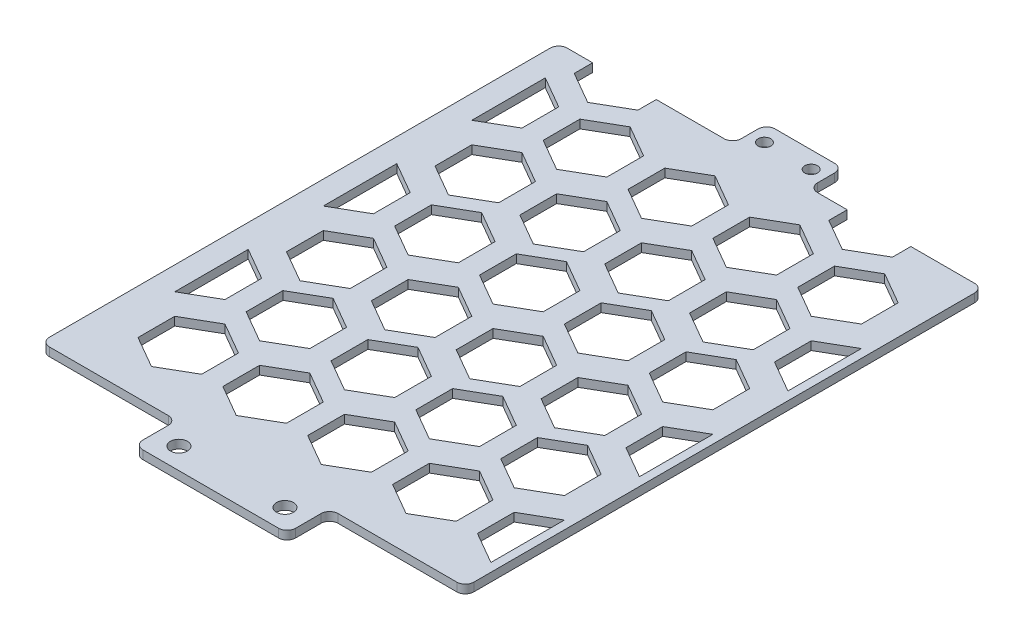
SolidWorks part; units mm, degrees
material "Thornel Mat VMA"
ref_plane "前视基准面" through (0, 0, 0) normal (0, 0, 1) x (1, 0, 0)
ref_plane "上视基准面" through (0, 0, 0) normal (0, 1, 0) x (1, 0, 0)
ref_plane "右视基准面" through (0, 0, 0) normal (1, 0, 0) x (0, 0, -1)
other "Configuration Table"
sketch "草图1" plane through (0, 0, 0) normal (0, 1, 0) x (1, 0, 0)
  line L0 (0, 0) -> (0, 39.2734) construction
  line L1 (50, -70) -> (18, -70)
  line L2 (50, -70) -> (50, 70)
  line L3 (50, 70) -> (-50, 70)
  line L4 (-50, -70) -> (-50, 70)
  line L5 (50, -70) -> (-50, 70) construction
  line L6 (50, 70) -> (-50, -70) construction
  line L7 (-18, -70) -> (-18, -80)
  line L8 (-18, -80) -> (18, -80)
  line L9 (18, -80) -> (18, -70)
  line L10 (0, -80) -> (0, -62.3533) construction
  line L11 (-18, -70) -> (-50, -70)
  circle A0 centre (-42.5, 66) radius 1.5
  circle A1 centre (42.5, 66) radius 1.5
  circle A2 centre (-12.5, -75) radius 2
  circle A3 centre (12.5, -75) radius 2
  point P0 (0, 0)
  dimension "D3" = 3
  dimension "D4" = 4
  dimension "D11" = 4
  dimension "D1" = 100
  dimension "D2" = 140
  dimension "D5" = 85
  dimension "D6" = 7.5
  dimension "D7" = 50
  dimension "D8" = 36
  dimension "D9" = 10
  dimension "D10" = 25
  dimension "D12" = 25
  dimension "D13" = 5
  dimension "D14" = 7.5
extrude "凸台-拉伸1" add sketch "草图1" along normal blind 2
sketch "草图4" plane through (0, 2, 0) normal (0, 1, 0) x (1, 0, 0)
  line L0 (50, 70) -> (-50, 70) construction
  line L1 (-50, 70) -> (50, 70)
  line L2 (-50, 70) -> (-50, 52)
  line L3 (-50, 52) -> (-9, 52)
  line L4 (50, 70) -> (50, 52)
  line L5 (-50, 70) -> (-50, -70) construction
  line L6 (0, 0) -> (0, 87.9983) construction
  line L7 (-9, 52) -> (-9, 60)
  line L8 (-9, 60) -> (9, 60)
  line L9 (9, 60) -> (9, 52)
  line L10 (9, 52) -> (50, 52)
  circle A0 centre (-5.5, 56) radius 1.5
  circle A1 centre (5.5, 56) radius 1.5
  dimension "D4" = 3
  dimension "D5" = 11
  dimension "D1" = 18
  dimension "D2" = 8
  dimension "D3" = 18
  dimension "D6" = 4
extrude "切除-拉伸3" cut sketch "草图4" against normal blind 10
sketch "草图5" plane through (0, 2, 0) normal (0, 1, 0) x (1, 0, 0)
  line L0 (-50, 52) -> (-9, 52) construction
  line L1 (-34.5, 43.3397) -> (-27, 47.6699)
  line L2 (-27, 47.6699) -> (-27, 56.3301)
  line L3 (-27, 56.3301) -> (-34.5, 60.6603)
  line L4 (-34.5, 60.6603) -> (-42, 56.3301)
  line L5 (-42, 56.3301) -> (-42, 47.6699)
  line L6 (-42, 47.6699) -> (-34.5, 43.3397)
  line L7 (-50, 52) -> (-50, -70) construction
  line L20 (25.5, 43.3397) -> (33, 47.6699)
  line L21 (33, 47.6699) -> (33, 56.3301)
  line L22 (33, 56.3301) -> (25.5, 60.6603)
  line L23 (25.5, 60.6603) -> (18, 56.3301)
  line L24 (18, 56.3301) -> (18, 47.6699)
  line L25 (18, 47.6699) -> (25.5, 43.3397)
  line L32 (-14.5, 43.3397) -> (-7, 47.6699) [skipped]
  line L33 (-7, 47.6699) -> (-7, 56.3301) [skipped]
  line L34 (-7, 56.3301) -> (-14.5, 60.6603) [skipped]
  line L35 (-14.5, 60.6603) -> (-22, 56.3301) [skipped]
  line L36 (-22, 56.3301) -> (-22, 47.6699) [skipped]
  line L37 (-22, 47.6699) -> (-14.5, 43.3397) [skipped]
  line L38 (5.5, 43.3397) -> (13, 47.6699) [skipped]
  line L39 (13, 47.6699) -> (13, 56.3301) [skipped]
  line L40 (13, 56.3301) -> (5.5, 60.6603) [skipped]
  line L41 (5.5, 60.6603) -> (-2, 56.3301) [skipped]
  line L42 (-2, 56.3301) -> (-2, 47.6699) [skipped]
  line L43 (-2, 47.6699) -> (5.5, 43.3397) [skipped]
  line L44 (45.5, 43.3397) -> (53, 47.6699) [skipped]
  line L45 (53, 47.6699) -> (53, 56.3301) [skipped]
  line L46 (53, 56.3301) -> (45.5, 60.6603) [skipped]
  line L47 (45.5, 60.6603) -> (38, 56.3301) [skipped]
  line L48 (38, 56.3301) -> (38, 47.6699) [skipped]
  line L49 (38, 47.6699) -> (45.5, 43.3397) [skipped]
  circle A0 centre (-34.5, 52) radius 7.5 construction
  dimension "D1" = 15
  dimension "D2" = 8
  dimension "D4" = 45
  dimension "D3" = 5
extrude "切除-拉伸4" cut sketch "草图5" against normal blind 3
sketch "草图7" plane through (0, 2, 0) normal (0, 1, 0) x (1, 0, 0)
  line L0 (-34.5, 43.3397) -> (-27, 47.6699) construction
  line L1 (-24.5, 43.3397) -> (-32, 39.0096)
  line L2 (-32, 39.0096) -> (-32, 30.3494)
  line L3 (-32, 30.3494) -> (-24.5, 26.0192)
  line L4 (-24.5, 26.0192) -> (-17, 30.3494)
  line L5 (-17, 30.3494) -> (-17, 39.0096)
  line L6 (-17, 39.0096) -> (-24.5, 43.3397)
  line L7 (-12, 8.0289) -> (-4.5, 12.359)
  line L8 (-32, 25.3494) -> (-39.5, 21.0192)
  line L9 (-39.5, 21.0192) -> (-39.5, 12.359)
  line L10 (-39.5, 12.359) -> (-32, 8.0289)
  line L11 (-32, 8.0289) -> (-24.5, 12.359)
  line L12 (-24.5, 12.359) -> (-24.5, 21.0192)
  line L13 (-24.5, 21.0192) -> (-32, 25.3494)
  line L14 (-4.5, 12.359) -> (-4.5, 21.0192)
  line L15 (-4.5, 21.0192) -> (-12, 25.3494)
  line L16 (-12, 25.3494) -> (-19.5, 21.0192)
  line L17 (-19.5, 21.0192) -> (-19.5, 12.359)
  line L18 (-19.5, 12.359) -> (-12, 8.0289)
  line L19 (-12, 30.3494) -> (-4.5, 26.0192)
  line L20 (-4.5, 26.0192) -> (3, 30.3494)
  line L21 (3, 30.3494) -> (3, 39.0096)
  line L22 (3, 39.0096) -> (-4.5, 43.3397)
  line L23 (-4.5, 43.3397) -> (-12, 39.0096)
  line L24 (-12, 39.0096) -> (-12, 30.3494)
  line L25 (8, 8.0289) -> (15.5, 12.359)
  line L26 (15.5, 12.359) -> (15.5, 21.0192)
  line L27 (15.5, 21.0192) -> (8, 25.3494)
  line L28 (8, 25.3494) -> (0.5, 21.0192)
  line L29 (0.5, 21.0192) -> (0.5, 12.359)
  line L30 (0.5, 12.359) -> (8, 8.0289)
  line L31 (8, 30.3494) -> (15.5, 26.0192)
  line L32 (15.5, 26.0192) -> (23, 30.3494)
  line L33 (23, 30.3494) -> (23, 39.0096)
  line L34 (23, 39.0096) -> (15.5, 43.3397)
  line L35 (15.5, 43.3397) -> (8, 39.0096)
  line L36 (8, 39.0096) -> (8, 30.3494)
  line L37 (28, 8.0289) -> (35.5, 12.359)
  line L38 (35.5, 12.359) -> (35.5, 21.0192)
  line L39 (35.5, 21.0192) -> (28, 25.3494)
  line L40 (28, 25.3494) -> (20.5, 21.0192)
  line L41 (20.5, 21.0192) -> (20.5, 12.359)
  line L42 (20.5, 12.359) -> (28, 8.0289)
  line L43 (28, 30.3494) -> (35.5, 26.0192)
  line L44 (35.5, 26.0192) -> (43, 30.3494)
  line L45 (43, 30.3494) -> (43, 39.0096)
  line L46 (43, 39.0096) -> (35.5, 43.3397)
  line L47 (35.5, 43.3397) -> (28, 39.0096)
  line L48 (28, 39.0096) -> (28, 30.3494)
  line L52 (48, 25.3494) -> (40.5, 21.0192)
  line L53 (40.5, 21.0192) -> (40.5, 12.359)
  line L54 (40.5, 12.359) -> (48, 8.0289)
  line L61 (-12, -26.9711) -> (-4.5, -22.641)
  line L62 (-4.5, -22.641) -> (-4.5, -13.9808)
  line L63 (-4.5, -13.9808) -> (-12, -9.6506)
  line L64 (-12, -9.6506) -> (-19.5, -13.9808)
  line L65 (-19.5, -13.9808) -> (-19.5, -22.641)
  line L66 (-19.5, -22.641) -> (-12, -26.9711)
  line L67 (-12, -4.6506) -> (-4.5, -8.9808)
  line L68 (-4.5, -8.9808) -> (3, -4.6506)
  line L69 (3, -4.6506) -> (3, 4.0096)
  line L70 (3, 4.0096) -> (-4.5, 8.3397)
  line L71 (-4.5, 8.3397) -> (-12, 4.0096)
  line L72 (-12, 4.0096) -> (-12, -4.6506)
  line L73 (8, -26.9711) -> (15.5, -22.641)
  line L74 (15.5, -22.641) -> (15.5, -13.9808)
  line L75 (15.5, -13.9808) -> (8, -9.6506)
  line L76 (8, -9.6506) -> (0.5, -13.9808)
  line L77 (0.5, -13.9808) -> (0.5, -22.641)
  line L78 (0.5, -22.641) -> (8, -26.9711)
  line L79 (8, -4.6506) -> (15.5, -8.9808)
  line L80 (15.5, -8.9808) -> (23, -4.6506)
  line L81 (23, -4.6506) -> (23, 4.0096)
  line L82 (23, 4.0096) -> (15.5, 8.3397)
  line L83 (15.5, 8.3397) -> (8, 4.0096)
  line L84 (8, 4.0096) -> (8, -4.6506)
  line L85 (28, -26.9711) -> (35.5, -22.641)
  line L86 (35.5, -22.641) -> (35.5, -13.9808)
  line L87 (35.5, -13.9808) -> (28, -9.6506)
  line L88 (28, -9.6506) -> (20.5, -13.9808)
  line L89 (20.5, -13.9808) -> (20.5, -22.641)
  line L90 (20.5, -22.641) -> (28, -26.9711)
  line L91 (28, -4.6506) -> (35.5, -8.9808)
  line L92 (35.5, -8.9808) -> (43, -4.6506)
  line L93 (43, -4.6506) -> (43, 4.0096)
  line L94 (43, 4.0096) -> (35.5, 8.3397)
  line L95 (35.5, 8.3397) -> (28, 4.0096)
  line L96 (28, 4.0096) -> (28, -4.6506)
  line L100 (48, -9.6506) -> (40.5, -13.9808)
  line L101 (40.5, -13.9808) -> (40.5, -22.641)
  line L102 (40.5, -22.641) -> (48, -26.9711)
  line L109 (-12, -61.9711) -> (-4.5, -57.641)
  line L110 (-4.5, -57.641) -> (-4.5, -48.9808)
  line L111 (-4.5, -48.9808) -> (-12, -44.6506)
  line L112 (-12, -44.6506) -> (-19.5, -48.9808)
  line L113 (-19.5, -48.9808) -> (-19.5, -57.641)
  line L114 (-19.5, -57.641) -> (-12, -61.9711)
  line L115 (-12, -39.6506) -> (-4.5, -43.9808)
  line L116 (-4.5, -43.9808) -> (3, -39.6506)
  line L117 (3, -39.6506) -> (3, -30.9904)
  line L118 (3, -30.9904) -> (-4.5, -26.6603)
  line L119 (-4.5, -26.6603) -> (-12, -30.9904)
  line L120 (-12, -30.9904) -> (-12, -39.6506)
  line L121 (8, -61.9711) -> (15.5, -57.641)
  line L122 (15.5, -57.641) -> (15.5, -48.9808)
  line L123 (15.5, -48.9808) -> (8, -44.6506)
  line L124 (8, -44.6506) -> (0.5, -48.9808)
  line L125 (0.5, -48.9808) -> (0.5, -57.641)
  line L126 (0.5, -57.641) -> (8, -61.9711)
  line L127 (8, -39.6506) -> (15.5, -43.9808)
  line L128 (15.5, -43.9808) -> (23, -39.6506)
  line L129 (23, -39.6506) -> (23, -30.9904)
  line L130 (23, -30.9904) -> (15.5, -26.6603)
  line L131 (15.5, -26.6603) -> (8, -30.9904)
  line L132 (8, -30.9904) -> (8, -39.6506)
  line L133 (28, -61.9711) -> (35.5, -57.641)
  line L134 (35.5, -57.641) -> (35.5, -48.9808)
  line L135 (35.5, -48.9808) -> (28, -44.6506)
  line L136 (28, -44.6506) -> (20.5, -48.9808)
  line L137 (20.5, -48.9808) -> (20.5, -57.641)
  line L138 (20.5, -57.641) -> (28, -61.9711)
  line L139 (28, -39.6506) -> (35.5, -43.9808)
  line L140 (35.5, -43.9808) -> (43, -39.6506)
  line L141 (43, -39.6506) -> (43, -30.9904)
  line L142 (43, -30.9904) -> (35.5, -26.6603)
  line L143 (35.5, -26.6603) -> (28, -30.9904)
  line L144 (28, -30.9904) -> (28, -39.6506)
  line L148 (48, -44.6506) -> (40.5, -48.9808)
  line L149 (40.5, -48.9808) -> (40.5, -57.641)
  line L150 (40.5, -57.641) -> (48, -61.9711)
  line L157 (-32, -26.9711) -> (-24.5, -22.641)
  line L158 (-24.5, -22.641) -> (-24.5, -13.9808)
  line L159 (-24.5, -13.9808) -> (-32, -9.6506)
  line L160 (-32, -9.6506) -> (-39.5, -13.9808)
  line L161 (-39.5, -13.9808) -> (-39.5, -22.641)
  line L162 (-39.5, -22.641) -> (-32, -26.9711)
  line L163 (-32, -4.6506) -> (-24.5, -8.9808)
  line L164 (-24.5, -8.9808) -> (-17, -4.6506)
  line L165 (-17, -4.6506) -> (-17, 4.0096)
  line L166 (-17, 4.0096) -> (-24.5, 8.3397)
  line L167 (-24.5, 8.3397) -> (-32, 4.0096)
  line L168 (-32, 4.0096) -> (-32, -4.6506)
  line L169 (-32, -61.9711) -> (-24.5, -57.641)
  line L170 (-24.5, -57.641) -> (-24.5, -48.9808)
  line L171 (-24.5, -48.9808) -> (-32, -44.6506)
  line L172 (-32, -44.6506) -> (-39.5, -48.9808)
  line L173 (-39.5, -48.9808) -> (-39.5, -57.641)
  line L174 (-39.5, -57.641) -> (-32, -61.9711)
  line L175 (-32, -39.6506) -> (-24.5, -43.9808)
  line L176 (-24.5, -43.9808) -> (-17, -39.6506)
  line L177 (-17, -39.6506) -> (-17, -30.9904)
  line L178 (-17, -30.9904) -> (-24.5, -26.6603)
  line L179 (-24.5, -26.6603) -> (-32, -30.9904)
  line L180 (-32, -30.9904) -> (-32, -39.6506)
  line L181 (48, 8.0289) -> (55.5, 12.359) [skipped]
  line L182 (55.5, 12.359) -> (55.5, 21.0192) [skipped]
  line L183 (55.5, 21.0192) -> (48, 25.3494) [skipped]
  line L184 (48, 30.3494) -> (55.5, 26.0192) [skipped]
  line L185 (55.5, 26.0192) -> (63, 30.3494) [skipped]
  line L186 (63, 30.3494) -> (63, 39.0096) [skipped]
  line L187 (63, 39.0096) -> (55.5, 43.3397) [skipped]
  line L188 (55.5, 43.3397) -> (48, 39.0096) [skipped]
  line L189 (48, -26.9711) -> (55.5, -22.641) [skipped]
  line L190 (55.5, -22.641) -> (55.5, -13.9808) [skipped]
  line L191 (55.5, -13.9808) -> (48, -9.6506) [skipped]
  line L192 (48, -4.6506) -> (55.5, -8.9808) [skipped]
  line L193 (55.5, -8.9808) -> (63, -4.6506) [skipped]
  line L194 (63, -4.6506) -> (63, 4.0096) [skipped]
  line L195 (63, 4.0096) -> (55.5, 8.3397) [skipped]
  line L196 (55.5, 8.3397) -> (48, 4.0096) [skipped]
  line L197 (48, -61.9711) -> (55.5, -57.641) [skipped]
  line L198 (55.5, -57.641) -> (55.5, -48.9808) [skipped]
  line L199 (55.5, -48.9808) -> (48, -44.6506) [skipped]
  line L200 (48, -39.6506) -> (55.5, -43.9808) [skipped]
  line L201 (55.5, -43.9808) -> (63, -39.6506) [skipped]
  line L202 (63, -39.6506) -> (63, -30.9904) [skipped]
  line L203 (63, -30.9904) -> (55.5, -26.6603) [skipped]
  line L204 (55.5, -26.6603) -> (48, -30.9904) [skipped]
  line L205 (48, 25.3494) -> (48, 8.0289)
  line L206 (48, -9.6506) -> (48, -26.9711)
  line L207 (48, -44.6506) -> (48, -61.9711)
  line L208 (-44.5, -43.9808) -> (-37, -39.6506)
  line L209 (48, -30.9904) -> (48, -39.6506) [skipped]
  line L210 (48, 4.0096) -> (48, -4.6506) [skipped]
  line L211 (48, 39.0096) -> (48, 30.3494) [skipped]
  line L212 (-37, -30.9904) -> (-44.5, -26.6603)
  line L213 (-37, -39.6506) -> (-37, -30.9904)
  line L214 (-44.5, -8.9808) -> (-37, -4.6506)
  line L215 (-37, -4.6506) -> (-37, 4.0096)
  line L216 (-37, 4.0096) -> (-44.5, 8.3397)
  line L217 (-44.5, 26.0192) -> (-37, 30.3494)
  line L218 (-37, 30.3494) -> (-37, 39.0096)
  line L219 (-37, 39.0096) -> (-44.5, 43.3397)
  line L220 (-44.5, 43.3397) -> (-44.5, 26.0192)
  line L221 (-44.5, 8.3397) -> (-44.5, -8.9808)
  line L222 (-44.5, -26.6603) -> (-44.5, -43.9808)
  circle A0 centre (-24.5, 34.6795) radius 7.5 construction
  circle A1 centre (-32, 16.6891) radius 7.5 construction
  dimension "D1" = 15
  dimension "D2" = 5
  dimension "D4" = 0
  dimension "D3" = 2.5
  dimension "D5" = 5
  dimension "D6" = 5
  dimension "D7" = 3
  dimension "D8" = 2
extrude "切除-拉伸5" cut sketch "草图7" against normal blind 3
fillet "圆角3" radius 2 12 edges at (9, 1, -60) (-50, 1, -52) (-50, 1, 70) (-18, 1, 70) (-18, 1, 80) (18, 1, 80) (18, 1, 70) (50, 1, 70) (50, 1, -52) (9, 1, -52) (-9, 1, -60) (-9, 1, -52)
